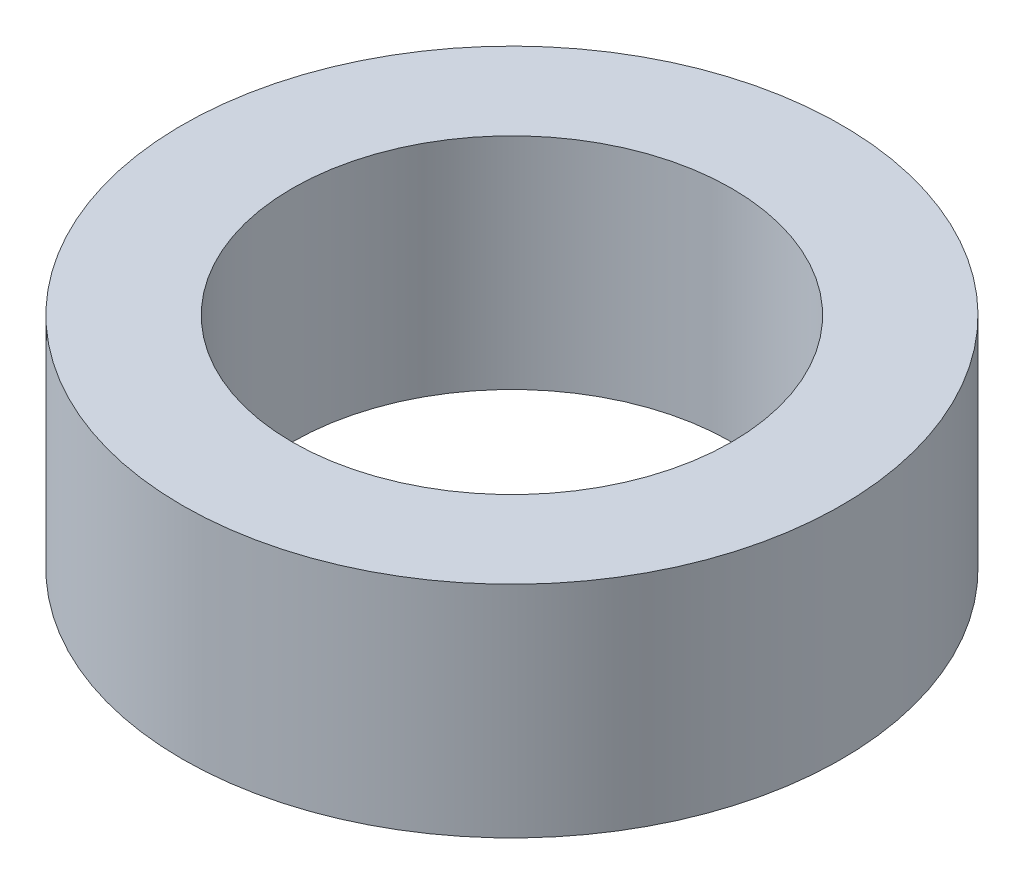
SolidWorks part; units mm, degrees
ref_plane "Front" through (0, 0, 0) normal (0, 0, 1) x (1, 0, 0)
ref_plane "Top" through (0, 0, 0) normal (0, 1, 0) x (1, 0, 0)
ref_plane "Right" through (0, 0, 0) normal (1, 0, 0) x (0, 0, -1)
sketch "Sketch1" plane through (0, 0, 0) normal (0, 1, 0) x (1, 0, 0)
  circle A0 centre (0, 0) radius 6
  circle A1 centre (0, 0) radius 9
extrude "Boss-Extrude1" add sketch "Sketch1" along normal blind 6
